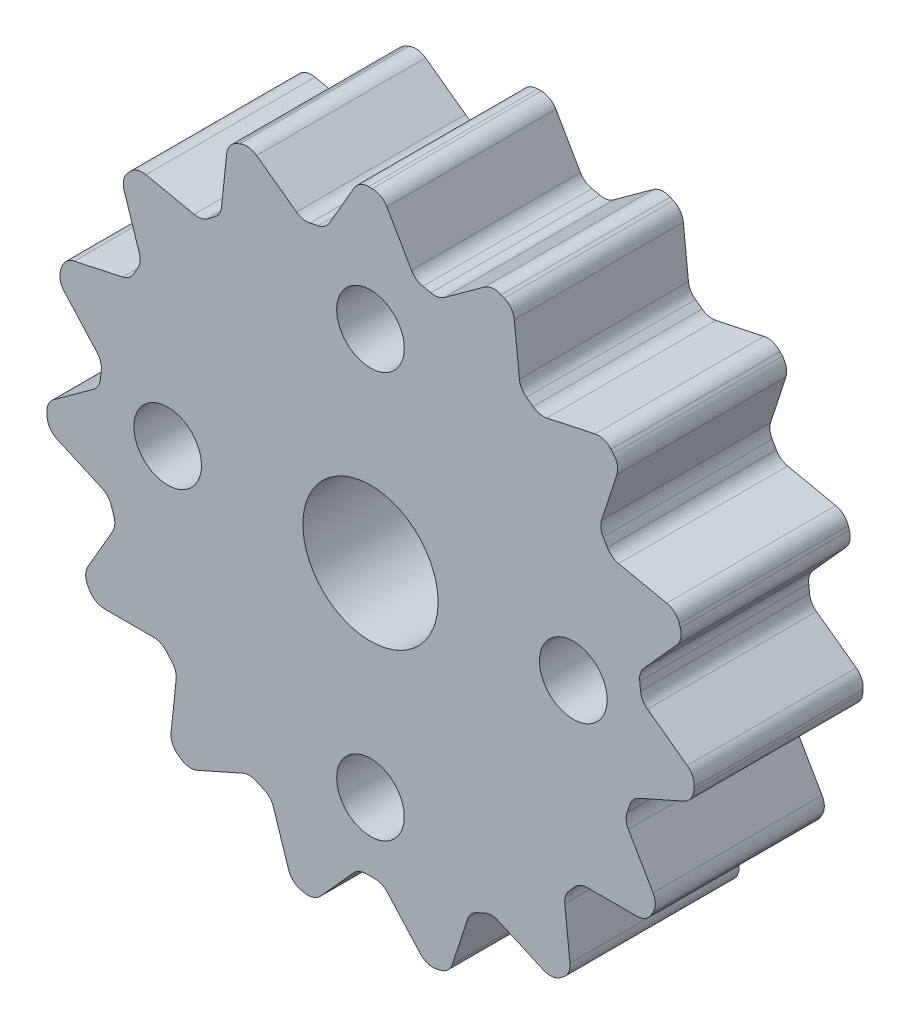
SolidWorks part; units mm, degrees
ref_plane "Front Plane" through (0, 0, 0) normal (0, 0, 1) x (1, 0, 0)
ref_plane "Top Plane" through (0, 0, 0) normal (0, 1, 0) x (1, 0, 0)
ref_plane "Right Plane" through (0, 0, 0) normal (1, 0, 0) x (0, 0, -1)
sketch "Sketch1" plane through (0, 0, 0) normal (0, 0, 1) x (1, 0, 0)
  line L0 (0, 0) -> (0, 6.1093) construction
  line L1 (0, 0) -> (-5.279, 24.8356) construction
  line L2 (0.2159, 6.1093) -> (-0.2159, 6.1093)
  line L3 (-0.2159, 6.1093) -> (-0.8431, 5.023)
  line L4 (0.2159, 6.1093) -> (0.8431, 5.023)
  circle A0 centre (0, 0) radius 5.0933 construction
  arc A1 (-0.8431, 5.023) -> (-1.059, 4.982) centre (0, 0) ccw
  arc A2 (-1.059, 4.982) -> (1.059, 4.982) centre (0, 5.0933) ccw
  arc A3 (0.8431, 5.023) -> (1.059, 4.982) centre (0, 0) cw
  point P3 (0, 5.0933)
  dimension "D1" = 12
  dimension "D5" = 0.2159
  dimension "D2" = 1.016
  dimension "D3" = 0.2159
  dimension "D4" = 30
extrude "Boss-Extrude1" add sketch "Sketch1" along normal blind 3.175
sketch "Sketch6" plane through (0, 0, 0) normal (0, 0, 1) x (1, 0, 0)
  circle A0 centre (0, 0) radius 5.0933
  arc A1 (-0.8431, 5.023) -> (-1.059, 4.982) centre (0, 0) ccw construction
extrude "Boss-Extrude2" add sketch "Sketch6" along normal blind 3.175
fillet "Fillet1" radius 0.3175 4 edges at (-0.8431, 5.023, 1.5875) (0.8431, 5.023, 1.5875) (0.2159, 6.1093, 1.5875) (-0.2159, 6.1093, 1.5875)
pattern_circular "CirPattern3" count 15 over 360 about axis through (0, 0, 0) along (0, 0, 1) of "Boss-Extrude1", "Fillet1"
sketch "Sketch7" plane through (0, 0, 3.175) normal (0, 0, 1) x (1, 0, 0)
  line L0 (-2.2478, 0) -> (2.2362, 0) construction
  line L1 (0, 1.7774) -> (0, -2.1069) construction
  circle A0 centre (0, 0) radius 1.27
  circle A1 centre (0, 3.81) radius 0.635
  circle A2 centre (-3.81, 0) radius 0.635
  circle A3 centre (3.81, 0) radius 0.635
  circle A4 centre (0, -3.81) radius 0.635
  dimension "D1" = 2.54
  dimension "D3" = 1.27
  dimension "D5" = 1.27
  dimension "D2" = 3.81
  dimension "D4" = 3.81
extrude "Cut-Extrude1" cut sketch "Sketch7" against normal blind 3.175
